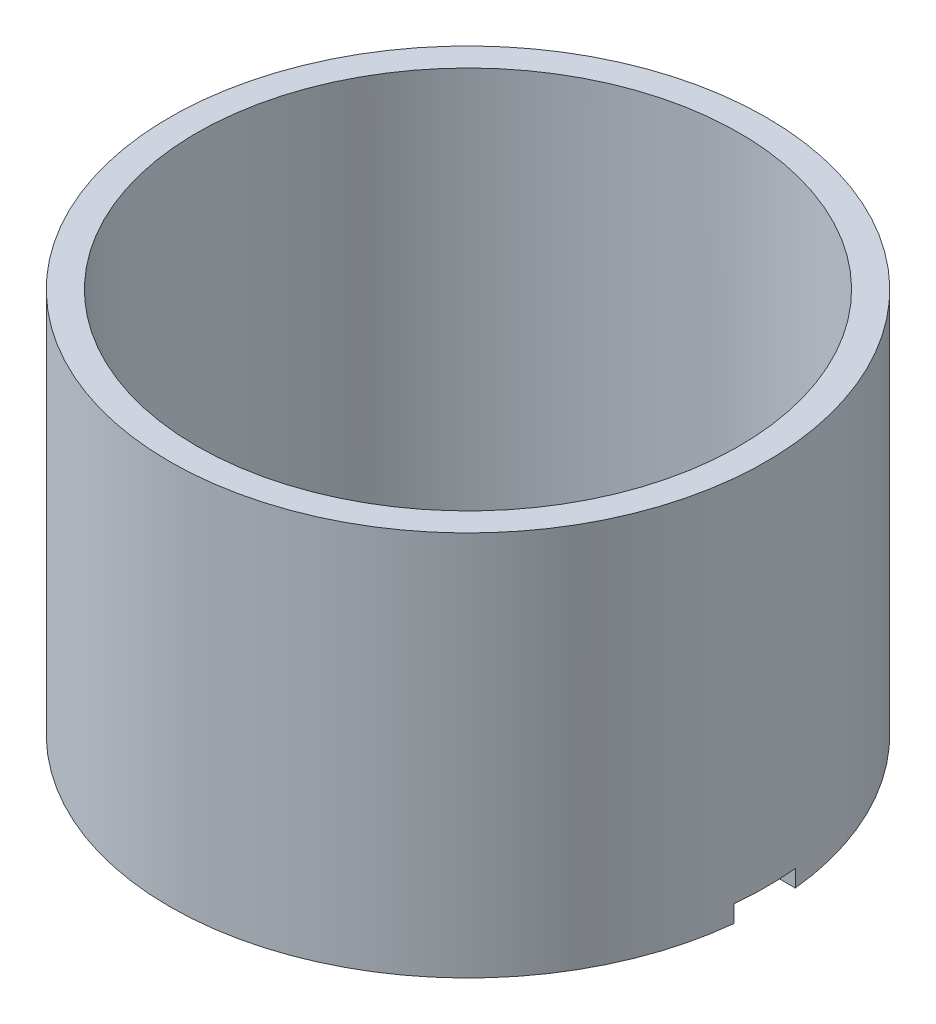
SolidWorks part; units mm, degrees
ref_plane "Front Plane" through (0, 0, 0) normal (0, 0, 1) x (1, 0, 0)
ref_plane "Top Plane" through (0, 0, 0) normal (0, 1, 0) x (1, 0, 0)
ref_plane "Right Plane" through (0, 0, 0) normal (1, 0, 0) x (0, 0, -1)
sketch "Sketch1" plane through (0, 0, 0) normal (0, 1, 0) x (1, 0, 0)
  circle A0 centre (0, 0) radius 9.55
  circle A1 centre (0, 0) radius 10.5
  dimension "D1" = 19.1
  dimension "D2" = 21
extrude "Boss-Extrude1" add sketch "Sketch1" along normal blind 12.97 and the other way blind 0.6
sketch "Sketch2" plane through (0, 0, 0) normal (1, 0, 0) x (0, 0, -1)
  line L4 (-1.08, -0.6174) -> (1.08, -0.6174)
  line L5 (-1.08, -0.6174) -> (-1.08, 0)
  line L6 (-1.08, 0) -> (1.08, 0)
  line L7 (1.08, -0.6174) -> (1.08, 0)
  dimension "D1" = 1.08
  dimension "D2" = 1.08
  dimension "D3" = 0.6174
extrude "Cut-Extrude1" cut sketch "Sketch2" against normal through all both and the other way through all
